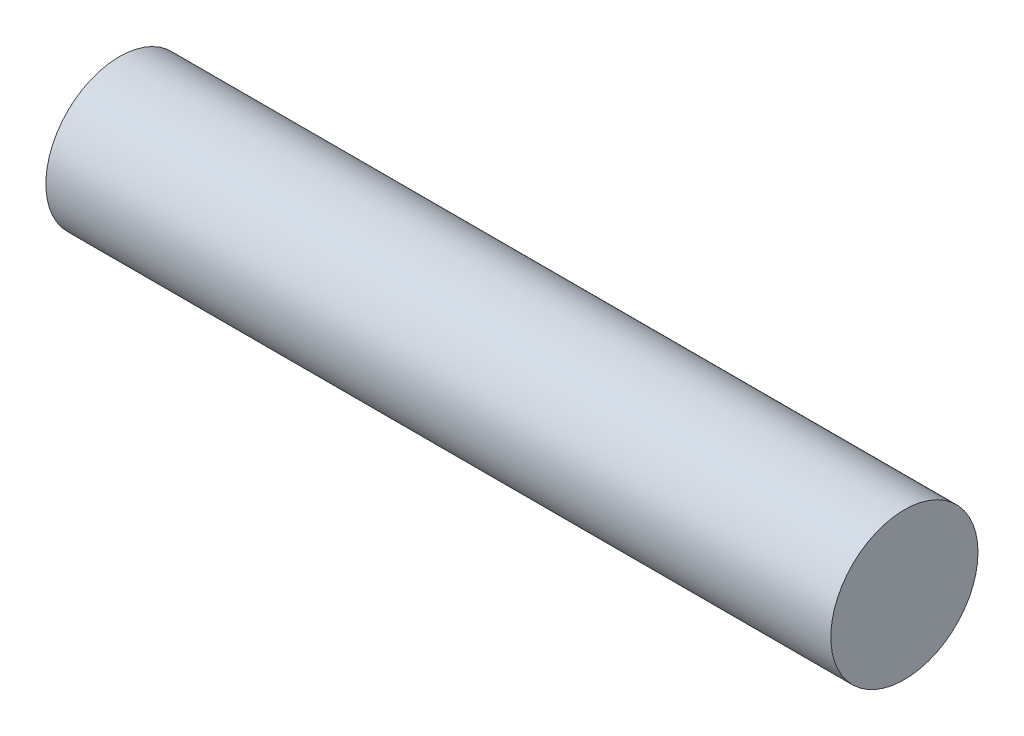
SolidWorks part; units mm, degrees
ref_plane "Front Plane" through (0, 0, 0) normal (0, 0, 1) x (1, 0, 0)
ref_plane "Top Plane" through (0, 0, 0) normal (0, 1, 0) x (1, 0, 0)
ref_plane "Right Plane" through (0, 0, 0) normal (1, 0, 0) x (0, 0, -1)
sketch "Sketch1" plane through (0, 0, 0) normal (1, 0, 0) x (0, 0, -1)
  circle A0 centre (0, 0) radius 2.3813
  dimension "D1" = 4.7625
extrude "Boss-Extrude1" add sketch "Sketch1" along normal blind 25.4
